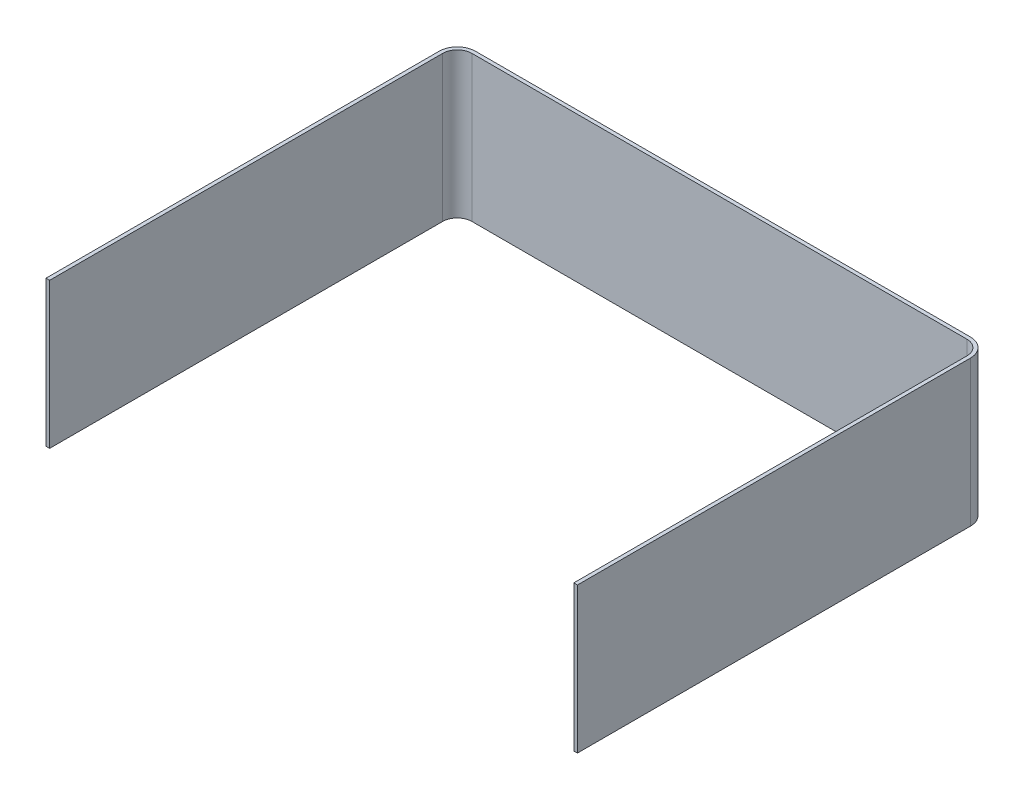
SolidWorks part; units mm, degrees
material "6061 Alloy"
ref_plane "Front Plane" through (0, 0, 0) normal (0, 0, 1) x (1, 0, 0)
ref_plane "Top Plane" through (0, 0, 0) normal (0, 1, 0) x (1, 0, 0)
ref_plane "Right Plane" through (0, 0, 0) normal (1, 0, 0) x (0, 0, -1)
sketch "Sketch1" plane through (0, 0, 0) normal (0, 1, 0) x (1, 0, 0)
  line L0 (-231.775, -180.975) -> (-231.775, 165.1)
  line L1 (-231.775, -177.8) -> (231.775, -177.8)
  line L2 (-228.6, -177.8) -> (-228.6, 165.1)
  line L3 (-215.9, 177.8) -> (215.9, 177.8)
  line L4 (228.6, -177.8) -> (228.6, 165.1)
  line L5 (-228.6, -177.8) -> (228.6, 177.8) construction
  line L6 (-228.6, 177.8) -> (228.6, -177.8) construction
  line L7 (-215.9, 180.975) -> (215.9, 180.975)
  line L8 (231.775, -180.975) -> (231.775, 165.1)
  line L9 (-231.775, -180.975) -> (231.775, -180.975)
  line L10 (-228.6, -177.8) -> (228.6, -177.8) construction
  arc A0 (215.9, 177.8) -> (228.6, 165.1) centre (215.9, 165.1) cw
  arc A1 (-228.6, 165.1) -> (-215.9, 177.8) centre (-215.9, 165.1) cw
  arc A2 (-231.775, 165.1) -> (-215.9, 180.975) centre (-215.9, 165.1) cw
  arc A3 (215.9, 180.975) -> (231.775, 165.1) centre (215.9, 165.1) cw
  point P0 (0, 0)
  dimension "D3" = 12.7
  dimension "D1" = 457.2
  dimension "D2" = 355.6
  dimension "D4" = 3.175
extrude "Boss-Extrude1" add sketch "Sketch1" along normal blind 127 contours A3 L7 A2 L0 L1 L2 A1 L3 A0 L4 L8
